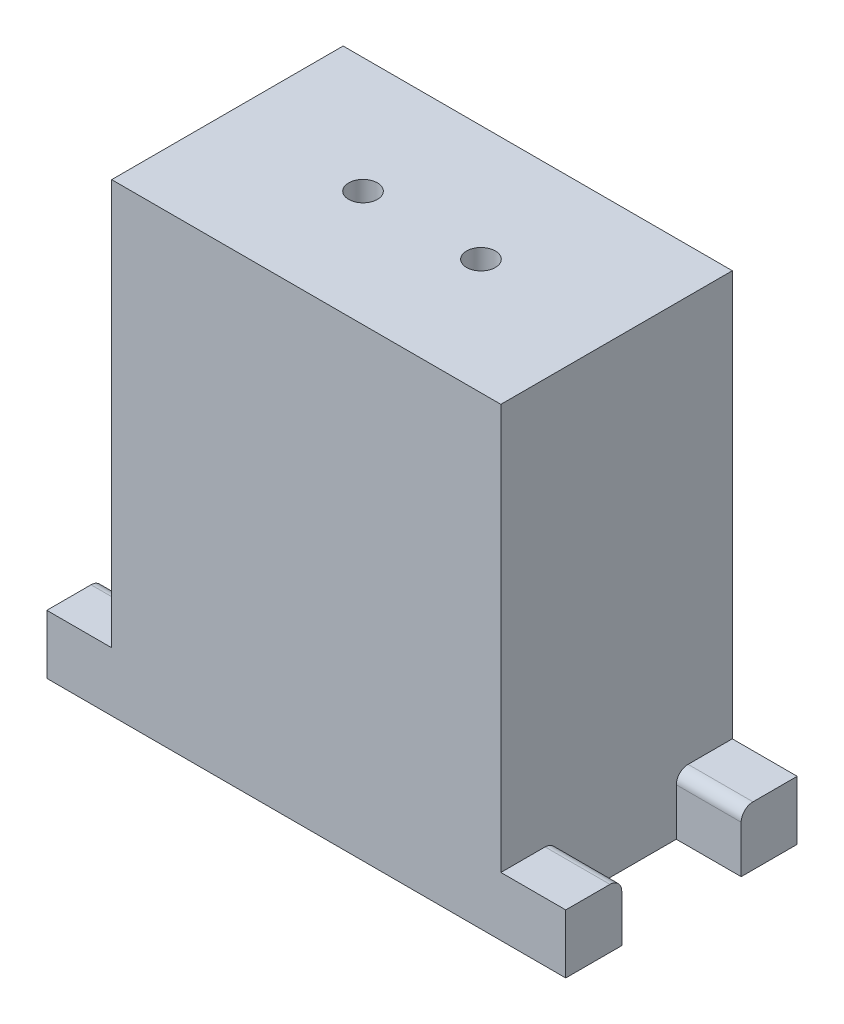
SolidWorks part; units mm, degrees
material "ABS"
ref_plane "正面" through (0, 0, 0) normal (0, 0, 1) x (1, 0, 0)
ref_plane "平面" through (0, 0, 0) normal (0, 1, 0) x (1, 0, 0)
ref_plane "右側面" through (0, 0, 0) normal (1, 0, 0) x (0, 0, -1)
sketch "ｽｹｯﾁ1" plane through (0, 0, 0) normal (0, 1, 0) x (1, 0, 0)
  line L1 (13.2, -7.85) -> (-13.2, -7.85)
  line L2 (13.2, -7.85) -> (13.2, 7.85)
  line L3 (13.2, 7.85) -> (-13.2, 7.85)
  line L4 (-13.2, -7.85) -> (-13.2, 7.85)
  line L5 (13.2, -7.85) -> (-13.2, 7.85) construction
  line L6 (13.2, 7.85) -> (-13.2, -7.85) construction
  point P0 (0, 0)
  dimension "D1" = 26.4
  dimension "D2" = 15.7
extrude "ﾎﾞｽ - 押し出し1" add sketch "ｽｹｯﾁ1" along normal blind 31.5
sketch "ｽｹｯﾁ2" plane through (13.2, 0, 0) normal (1, 0, 0) x (0, 0, -1)
  line L0 (-7.85, 0) -> (7.85, 0) construction
  line L1 (-4.05, 4) -> (-7.85, 4)
  line L2 (-4.05, 4) -> (-4.05, 0)
  line L3 (-4.05, 0) -> (-7.85, 0)
  line L4 (-7.85, 4) -> (-7.85, 0)
  line L5 (-4.05, 4) -> (-7.85, 0) construction
  line L6 (-4.05, 0) -> (-7.85, 4) construction
  line L7 (4.05, 4) -> (7.85, 4)
  line L8 (4.05, 4) -> (4.05, 0)
  line L9 (4.05, 0) -> (7.85, 0)
  line L10 (7.85, 4) -> (7.85, 0)
  line L11 (4.05, 4) -> (7.85, 0) construction
  line L12 (4.05, 0) -> (7.85, 4) construction
  point P0 (-5.95, 2)
  point P6 (5.95, 2)
  point P12 (2.3488, 0)
  point P15 (2.6169, 5.4762)
  dimension "D1" = 3.8
  dimension "D2" = 4
extrude "ﾎﾞｽ - 押し出し2" add sketch "ｽｹｯﾁ2" along normal blind 4.4
sketch "ｽｹｯﾁ3" plane through (-13.2, 0, 0) normal (-1, 0, 0) x (0, 0, 1)
  line L1 (4.05, 4) -> (7.85, 4)
  line L2 (4.05, 4) -> (4.05, 0)
  line L3 (4.05, 0) -> (7.85, 0)
  line L4 (7.85, 4) -> (7.85, 0)
  line L5 (4.05, 4) -> (7.85, 0) construction
  line L6 (4.05, 0) -> (7.85, 4) construction
  line L7 (-4.05, 4) -> (-7.85, 4)
  line L8 (-4.05, 4) -> (-4.05, 0)
  line L9 (-4.05, 0) -> (-7.85, 0)
  line L10 (-7.85, 4) -> (-7.85, 0)
  line L11 (-4.05, 4) -> (-7.85, 0) construction
  line L12 (-4.05, 0) -> (-7.85, 4) construction
  point P0 (5.95, 2)
  point P6 (-5.95, 2)
  dimension "D1" = 3.8
  dimension "D2" = 4
extrude "ﾎﾞｽ - 押し出し3" add sketch "ｽｹｯﾁ3" along normal blind 4.4
sketch "ｽｹｯﾁ4" plane through (0, 0, 0) normal (0, -1, 0) x (1, 0, 0)
  line L0 (13.2, 0) -> (-13.2, 0) construction
  line L1 (13.2, 4.05) -> (13.2, -4.05) construction
  line L2 (-13.2, -4.05) -> (-13.2, 4.05) construction
  circle A0 centre (4, 0) radius 0.975
  circle A1 centre (-4, 0) radius 0.975
  dimension "D2" = 4
  dimension "D3" = 1.95
  dimension "D1" = 4
extrude "ｶｯﾄ - 押し出し1" cut sketch "ｽｹｯﾁ4" against normal through all
fillet "ﾌｨﾚｯﾄ1" radius 0.8 4 edges at (15.4, 4, 4.05) (15.4, 4, -4.05) (-15.4, 4, 4.05) (-15.4, 4, -4.05)
